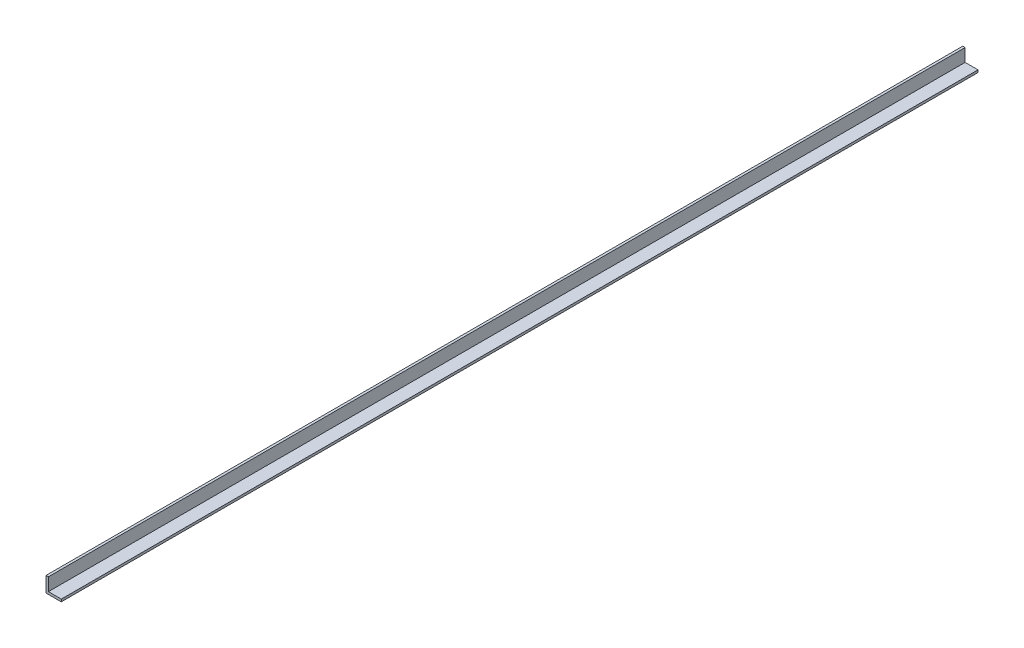
SolidWorks part; units mm, degrees
material "ASTM A36 Acero"
ref_plane "Alzado" through (0, 0, 0) normal (0, 0, 1) x (1, 0, 0)
ref_plane "Planta" through (0, 0, 0) normal (0, 1, 0) x (1, 0, 0)
ref_plane "Vista lateral" through (0, 0, 0) normal (1, 0, 0) x (0, 0, -1)
sketch "Croquis1" plane through (0, 0, 0) normal (0, 0, 1) x (1, 0, 0)
  line L0 (0, 101.6) -> (0, 0)
  line L1 (0, 0) -> (101.6, 0)
  line L2 (101.6, 0) -> (101.6, 15.88)
  line L3 (101.6, 15.88) -> (15.88, 15.88)
  line L4 (15.88, 15.88) -> (15.88, 101.6)
  line L5 (15.88, 101.6) -> (0, 101.6)
  dimension "D1" = 15.88
  dimension "D2" = 101.6
extrude "Saliente-Extruir1" add sketch "Croquis1" against normal blind 6100
